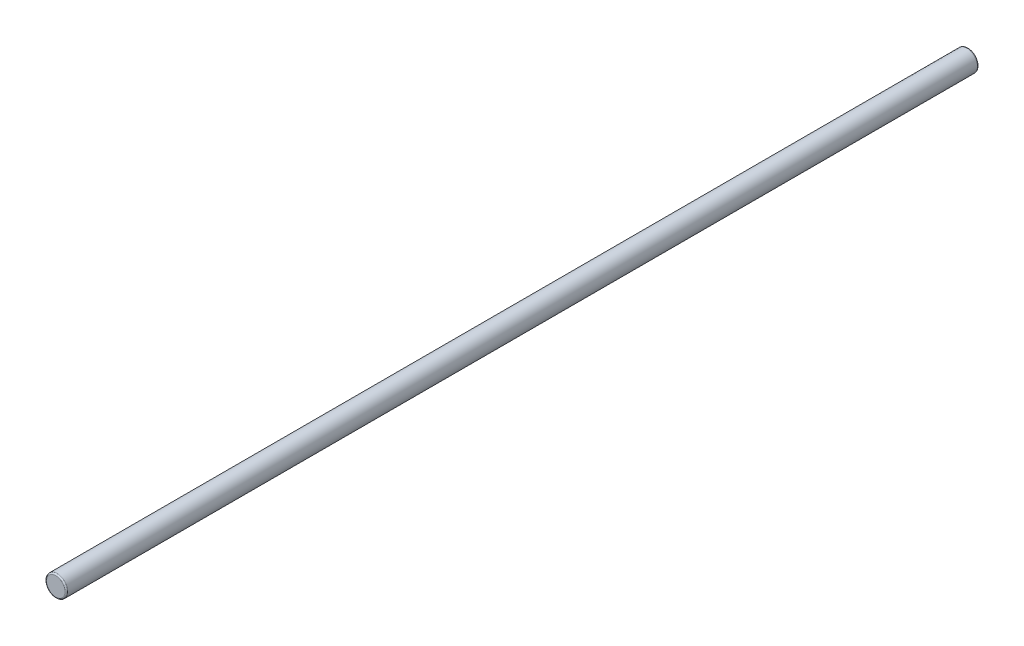
SolidWorks part; units mm, degrees
ref_plane "Alzado" through (0, 0, 0) normal (0, 0, 1) x (1, 0, 0)
ref_plane "Planta" through (0, 0, 0) normal (0, 1, 0) x (1, 0, 0)
ref_plane "Vista lateral" through (0, 0, 0) normal (1, 0, 0) x (0, 0, -1)
sketch "Croquis1" plane through (0, 0, 0) normal (0, 0, 1) x (1, 0, 0)
  circle A0 centre (0, 0) radius 4
  dimension "D1" = 8
extrude "Saliente-Extruir1" add sketch "Croquis1" along normal blind 345
fillet "Redondeo1" radius 0.5 2 edges at (4, 0, 0) (4, 0, 345)
